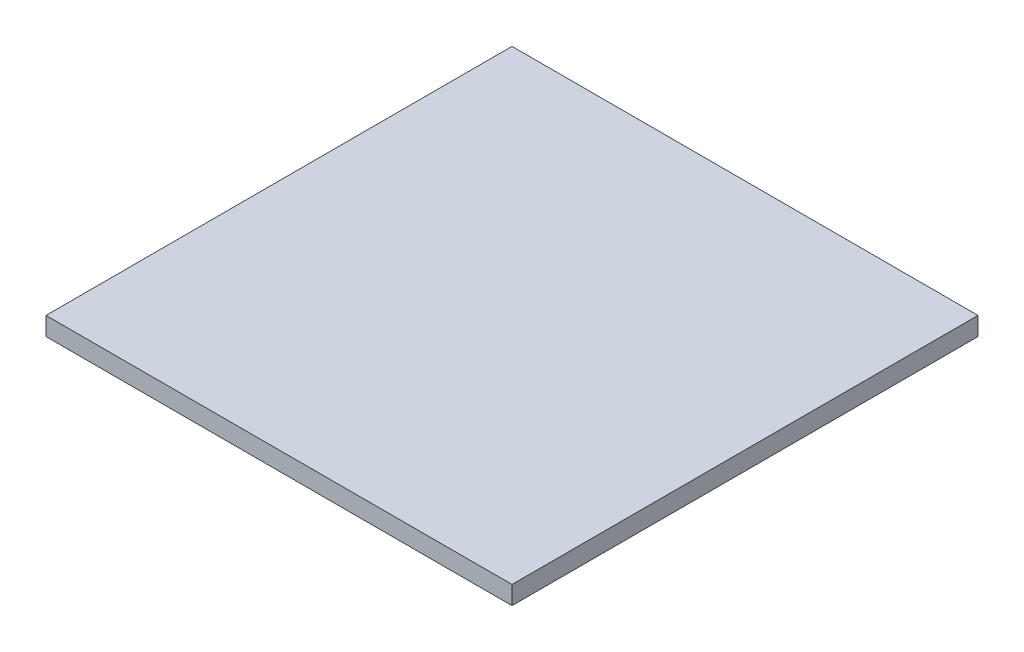
SolidWorks part; units mm, degrees
ref_plane "Front Plane" through (0, 0, 0) normal (0, 0, 1) x (1, 0, 0)
ref_plane "Top Plane" through (0, 0, 0) normal (0, 1, 0) x (1, 0, 0)
ref_plane "Right Plane" through (0, 0, 0) normal (1, 0, 0) x (0, 0, -1)
sketch "Sketch1" plane through (0, 0, 0) normal (0, 1, 0) x (1, 0, 0)
  line L1 (0, 0) -> (12.7, 0)
  line L2 (0, 0) -> (0, 12.7)
  line L3 (0, 12.7) -> (12.7, 12.7)
  line L4 (12.7, 0) -> (12.7, 12.7)
  dimension "D1" = 12.7
  dimension "D2" = 12.7
extrude "Boss-Extrude1" add sketch "Sketch1" along normal blind 0.5
